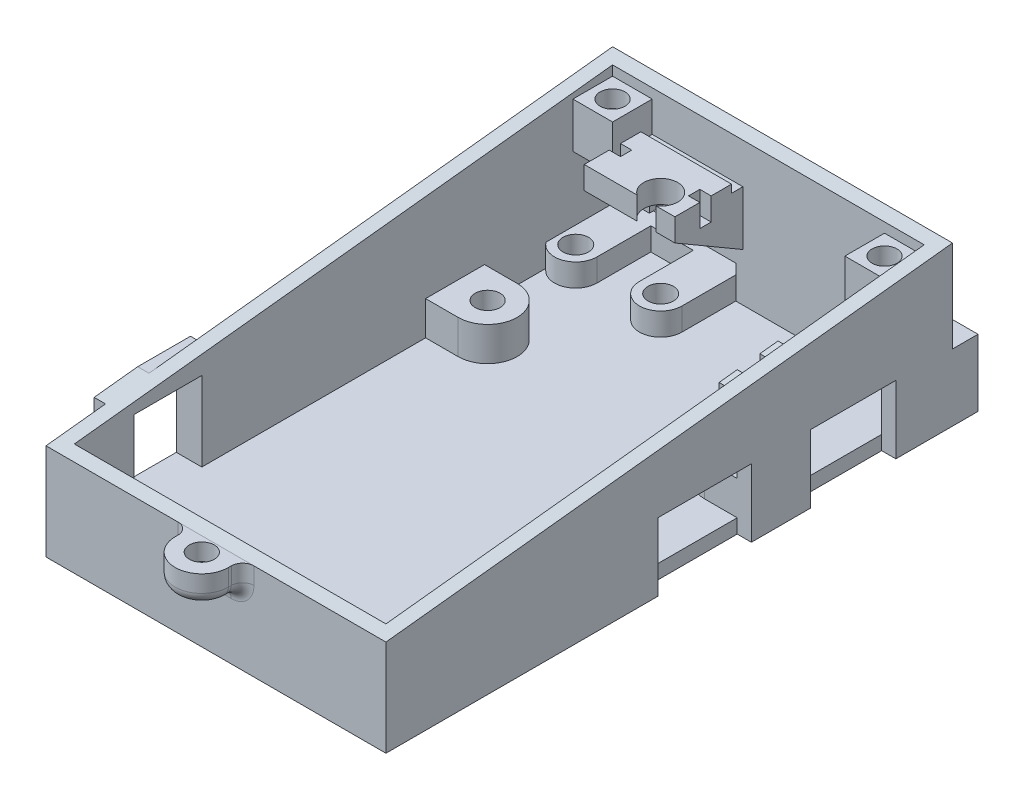
SolidWorks part; units mm, degrees
ref_plane "前视基准面" through (0, 0, 0) normal (0, 0, 1) x (1, 0, 0)
ref_plane "上视基准面" through (0, 0, 0) normal (0, 1, 0) x (1, 0, 0)
ref_plane "右视基准面" through (0, 0, 0) normal (1, 0, 0) x (0, 0, -1)
other "Configuration Table"
sketch "草图1" plane through (0, 0, 0) normal (1, 0, 0) x (0, 0, -1)
  line L0 (0, 0) -> (100, 0)
  line L1 (100, 0) -> (100, 28)
  line L2 (100, 28) -> (0, 17)
  line L3 (0, 17) -> (0, 0)
  dimension "D1" = 100
  dimension "D2" = 28
  dimension "D3" = 17
extrude "凸台-拉伸1" add sketch "草图1" along normal blind 60 contours L3 L0 L1 L2
sketch "草图2" plane through (0, 0, 0) normal (-1, 0, 0) x (0, 0, 1)
  line L0 (0, 17) -> (0, 0) construction
  line L1 (-100, 0) -> (0, 0)
  line L2 (-100, 0) -> (-100, 28)
  line L3 (-97.5, 2.5) -> (-2.5, 2.5)
  line L4 (0, 0) -> (0, 17)
  line L5 (-100, 28) -> (-97.5, 27.725)
  line L6 (-100, 0) -> (-97.5, 0)
  line L7 (-100, 0) -> (-100, 28)
  line L9 (-97.5, 2.5) -> (-97.5, 27.725)
  line L10 (-100, 28) -> (0, 17) construction
  line L11 (-2.5, 17.275) -> (0, 17)
  line L12 (0, 0) -> (-2.5, 0)
  line L13 (0, 0) -> (0, 17)
  line L15 (-2.5, 2.5) -> (-2.5, 17.275)
  dimension "D1" = 2.5
  dimension "D2" = 2.5
  dimension "D3" = 2.5
shell "抽壳1" thickness 2.5
sketch "草图3" plane through (0, 2.5, 0) normal (0, 1, 0) x (1, 0, 0)
  line L0 (30, 97.5) -> (30, 2.5) construction
  line L1 (57.5, 97.5) -> (2.5, 97.5) construction
  line L2 (57.5, 2.5) -> (2.5, 2.5) construction
  line L3 (2.5, 88) -> (64.282, 88) construction
  line L4 (60, 100) -> (0, 100) construction
  line L5 (2.5, 97.5) -> (2.5, 2.5) construction
  line L6 (2.5, 97.5) -> (2.5, 85.75)
  line L7 (2.5, 2.5) -> (2.5, 97.5) construction
  line L8 (9.25, 88) -> (9.25, 97.5)
  line L9 (9.25, 97.5) -> (2.5, 97.5)
  line L10 (16.75, 88) -> (16.75, 97.5)
  line L11 (24.25, 88) -> (24.25, 97.5)
  line L12 (24.25, 97.5) -> (16.75, 97.5)
  line L13 (57.5, 97.5) -> (2.5, 97.5) construction
  circle A0 centre (5.5, 88) radius 2.25
  circle A1 centre (20.5, 88) radius 2.25
  arc A2 (2.5, 85.75) -> (9.25, 88) centre (5.5, 88) ccw
  arc A3 (16.75, 88) -> (24.25, 88) centre (20.5, 88) ccw
  circle A4 centre (5.5, 88) radius 3.75 construction
  circle A5 centre (20.5, 88) radius 3.75 construction
  dimension "D2" = 4.5
  dimension "D1" = 12
  dimension "D3" = 3
  dimension "D4" = 15
  dimension "D5" = 1.5
extrude "凸台-拉伸3" add sketch "草图3" along normal blind 4
sketch "草图4" plane through (0, 0, -97.5) normal (0, 0, 1) x (1, 0, 0)
  line L0 (13, 2.5) -> (13, 21.6286) construction
  line L1 (16.75, 2.5) -> (9.25, 2.5) construction
  line L2 (2.5, 6.5) -> (24.25, 6.5) construction
  line L3 (17, 8.3) -> (24.25, 8.3)
  line L5 (9, 8.3) -> (9, 13)
  line L6 (9, 13) -> (17, 13)
  line L7 (17, 8.3) -> (17, 13)
  line L8 (2.5, 6.5) -> (24.25, 6.5)
  line L9 (2.5, 6.5) -> (2.5, 8.3)
  line L10 (2.5, 8.3) -> (9, 8.3)
  line L11 (24.25, 6.5) -> (24.25, 8.3)
  dimension "D1" = 8
  dimension "D2" = 6.5
  dimension "D3" = 1.8
extrude "切除-拉伸1" cut sketch "草图4" against normal through all
sketch "草图5" plane through (0, 2.5, 0) normal (0, 1, 0) x (1, 0, 0)
  line L0 (30, 2.5) -> (30, 97.5) construction
  line L1 (57.5, 2.5) -> (2.5, 2.5) construction
  line L2 (57.5, 97.5) -> (2.5, 97.5) construction
  line L3 (57.5, 2.5) -> (2.5, 2.5) construction
  line L4 (8.25, 2.5) -> (8.25, 69.7) construction
  line L5 (51.75, 2.5) -> (51.75, 69.7) construction
  line L6 (5.0329, 2.5) -> (11.4671, 2.5)
  line L7 (48.5329, 2.5) -> (54.9671, 2.5)
  line L8 (8.25, 74.9) -> (2.5, 74.9)
  line L9 (2.5, 97.5) -> (2.5, 2.5) construction
  line L10 (2.5, 74.9) -> (2.5, 64.5)
  line L11 (2.5, 2.5) -> (2.5, 85.75) construction
  line L12 (2.5, 64.5) -> (8.25, 64.5)
  line L13 (51.75, 74.9) -> (57.5, 74.9)
  line L14 (57.5, 74.9) -> (57.5, 64.5)
  line L15 (57.5, 64.5) -> (51.75, 64.5)
  circle A0 centre (8.25, 5.2) radius 2.2
  circle A1 centre (51.75, 5.2) radius 2.2
  arc A2 (11.4671, 2.5) -> (5.0329, 2.5) centre (8.25, 5.2) ccw
  arc A3 (48.5329, 2.5) -> (54.9671, 2.5) centre (51.75, 5.2) cw
  circle A4 centre (8.25, 5.2) radius 4.2 construction
  circle A5 centre (8.25, 69.7) radius 2.2
  arc A6 (8.25, 64.5) -> (8.25, 74.9) centre (8.25, 69.7) ccw
  circle A7 centre (8.25, 69.7) radius 5.2 construction
  arc A8 (51.75, 64.5) -> (51.75, 74.9) centre (51.75, 69.7) cw
  circle A9 centre (51.75, 69.7) radius 2.2
  dimension "D2" = 4.4
  dimension "D5" = 4.4
  dimension "D8" = 2
  dimension "D1" = 43.5
  dimension "D3" = 2.7
  dimension "D6" = 64.5
  dimension "D4" = 2
  dimension "D7" = 3
extrude "凸台-拉伸4" add sketch "草图5" along normal blind 6
sketch "草图6" plane through (0, 0, 0) normal (-1, 0, 0) x (0, 0, 1)
  line L0 (-100, 0) -> (0, 0) construction
  line L1 (-90, 0) -> (-48, 0)
  line L2 (-90, 0) -> (-90, 12)
  line L3 (-90, 12) -> (-48, 12)
  line L4 (-48, 0) -> (-48, 12)
  line L5 (-100, 0) -> (-100, 28) construction
  dimension "D1" = 10
  dimension "D2" = 52
  dimension "D3" = 12
sketch "草图7" plane through (60, 0, 0) normal (1, 0, 0) x (0, 0, -1)
  line L25 (90, 0) -> (90, 12)
  line L26 (48, 0) -> (90, 0)
  line L27 (48, 12) -> (48, 0)
  line L28 (90, 12) -> (48, 12)
  line L29 (90, 0) -> (90, 12)
  line L30 (48, 0) -> (90, 0)
  line L31 (48, 12) -> (48, 0)
  line L32 (90, 12) -> (48, 12)
  dimension "D1" = 0
extrude "切除-拉伸3" cut sketch "草图7" against normal up to surface (2.5 mm away) up to face at (57.5, 9, -59.85)
sketch "草图8" plane through (57.5, 0, 0) normal (1, 0, 0) x (0, 0, -1)
  line L0 (90, 12) -> (48, 12) construction
  line L1 (64.5, 12) -> (74.9, 12)
  line L2 (64.5, 12) -> (64.5, 0)
  line L3 (64.5, 0) -> (74.9, 0)
  line L4 (74.9, 12) -> (74.9, 0)
  line L5 (100, 0) -> (0, 0) construction
  line L6 (74.9, 8.5) -> (74.9, 2.5) construction
  line L7 (64.5, 8.5) -> (64.5, 2.5) construction
extrude "凸台-拉伸5" add sketch "草图8" along normal up to surface (2.5 mm away) up to face at (60, 8.625, -59.5)
ref_plane "基准面5" through (0, 28, 0) normal (0, 1, 0) x (1, 0, 0)
ref_plane "基准面6" through (0, 18, 0) normal (0, 1, 0) x (1, 0, 0)
sketch "草图9" plane through (0, 18, 0) normal (0, 1, 0) x (1, 0, 0)
  line L0 (2.5, 94) -> (9.5, 94) construction
  line L1 (2.5, 97.5) -> (9.5, 97.5)
  line L2 (2.5, 97.5) -> (2.5, 90.5)
  line L3 (2.5, 90.5) -> (9.5, 90.5)
  line L4 (9.5, 97.5) -> (9.5, 90.5)
  line L5 (6, 97.5) -> (6, 90.5) construction
  circle A0 centre (6, 94) radius 2.2
  dimension "D1" = 4.4
  dimension "D2" = 7
  dimension "D3" = 7
extrude "凸台-拉伸6" add sketch "草图9" along normal offset from surface (8 mm away) 2 up to plane "基准面5"
sketch "草图10" plane through (0, 18, 0) normal (0, -1, 0) x (1, 0, 0)
  circle A0 centre (6, -94) radius 2.2
extrude "凸台-拉伸7" add sketch "草图10" against normal blind 5
sketch "草图11" plane through (0, 18, 0) normal (0, -1, 0) x (1, 0, 0)
  line L0 (17.5, -85.5) -> (17.5, -97.5) construction
  line L1 (9.5, -97.5) -> (25.5, -97.5)
  line L2 (9.5, -97.5) -> (9.5, -91.9)
  line L3 (9.5, -85.5) -> (25.5, -85.5)
  line L4 (25.5, -97.5) -> (25.5, -91.9)
  line L5 (9.5, -89.9) -> (11.5, -89.9)
  line L7 (9.5, -91.9) -> (11.5, -91.9)
  line L8 (11.5, -89.9) -> (11.5, -91.9)
  line L9 (25.5, -89.9) -> (23.5, -89.9)
  line L11 (25.5, -91.9) -> (23.5, -91.9)
  line L12 (23.5, -89.9) -> (23.5, -91.9)
  line L13 (25.5, -89.9) -> (25.5, -85.5)
  line L14 (9.5, -89.9) -> (9.5, -85.5)
  dimension "D1" = 16
  dimension "D2" = 12
  dimension "D3" = 2
  dimension "D4" = 12
  dimension "D5" = 5.6
extrude "凸台-拉伸8" add sketch "草图11" against normal offset from surface (4 mm away) 4 up to face at (6, 26, -91.8)
sketch "草图13" plane through (25.5, 0, 0) normal (1, 0, 0) x (0, 0, -1)
  line L0 (85.5, 18) -> (97.5, 11)
  line L1 (33, 18) -> (-33, 18) construction
  line L2 (97.5, 2.5) -> (97.5, 27.725) construction
  line L3 (97.5, 11) -> (97.5, 18)
  line L4 (97.5, 18) -> (85.5, 18)
  line L5 (85.5, 22) -> (85.5, 18) construction
  dimension "D1" = 7
extrude "凸台-拉伸10" add sketch "草图13" against normal blind 4
sketch "草图14" plane through (0, 6.5, 0) normal (0, 1, 0) x (1, 0, 0)
  circle A0 centre (20.5, 88) radius 3
  dimension "D1" = 6
extrude "切除-拉伸4" cut sketch "草图14" along normal through all
sketch "草图15" plane through (0, 22, 0) normal (0, 1, 0) x (1, 0, 0)
  line L0 (25.5, 97.5) -> (25.5, 91.9) construction
  line L1 (9.5, 97.5) -> (25.5, 97.5)
  line L2 (9.5, 97.5) -> (9.5, 95.5)
  line L3 (9.5, 95.5) -> (25.5, 95.5)
  line L4 (25.5, 97.5) -> (25.5, 95.5)
  dimension "D1" = 2
extrude "切除-拉伸5" cut sketch "草图15" against normal blind 1.4
ref_plane "基准面7" through (30, 0, 0) normal (-1, 0, 0) x (0, 0, 1)
mirror "镜向2" about plane through (30, 0, 0) normal (-1, 0, 0) of "凸台-拉伸6"
sketch "草图16" plane through (0, 0, 0) normal (-1, 0, 0) x (0, 0, 1)
  line L0 (-97.5, 2.5) -> (-2.5, 2.5) construction
  line L1 (-13, 16.5) -> (-25, 16.5)
  line L2 (-13, 16.5) -> (-13, 2.5)
  line L3 (-13, 2.5) -> (-25, 2.5)
  line L4 (-25, 16.5) -> (-25, 2.5)
  line L5 (0, 0) -> (0, 17) construction
  dimension "D1" = 13
  dimension "D2" = 12
  dimension "D3" = 14
extrude "切除-拉伸6" cut sketch "草图16" against normal up to surface (2.5 mm away)
sketch "草图17" plane through (0, 0, 0) normal (-1, 0, 0) x (0, 0, 1)
  line L0 (-27.5, 0) -> (-10.5, 0)
  line L1 (-25, 2.5) -> (-13, 2.5)
  line L2 (-25, 2.5) -> (-25, 16.5)
  line L3 (-25, 16.5) -> (-13, 16.5)
  line L4 (-13, 2.5) -> (-13, 16.5)
  line L5 (-10.5, 0) -> (-10.5, 18.155)
  line L6 (-27.5, 19) -> (-18.1818, 19)
  line L7 (-27.5, 0) -> (-27.5, 19)
  line L8 (-18.1818, 19) -> (-10.5, 18.155)
  line L9 (-100, 28) -> (0, 17) construction
  line L10 (-10.5, 0) -> (-10.5, 19) construction
  line L11 (-27.5, 19) -> (-10.5, 19) construction
  dimension "D1" = 2.5
extrude "凸台-拉伸14" add sketch "草图17" along normal blind 2
sketch "草图18" plane through (0, 8.5, 0) normal (0, 1, 0) x (1, 0, 0)
  line L1 (57.5, 74.9) -> (54.3, 74.9)
  line L2 (57.5, 74.9) -> (57.5, 71.7)
  line L3 (57.5, 71.7) -> (54.3, 71.7)
  line L4 (54.3, 74.9) -> (54.3, 71.7)
  line L5 (57.5, 64.5) -> (54.3, 64.5)
  line L6 (57.5, 64.5) -> (57.5, 67.7)
  line L7 (57.5, 67.7) -> (54.3, 67.7)
  line L8 (54.3, 64.5) -> (54.3, 67.7)
  dimension "D1" = 3.2
extrude "凸台-拉伸15" add sketch "草图18" along normal offset from surface (14.2239 mm away) 2.5
sketch "草图19" plane through (0, 8.5, 0) normal (0, 1, 0) x (1, 0, 0)
  line L1 (57.5, 74.9) -> (51.75, 74.9)
  line L2 (57.5, 74.9) -> (57.5, 64.5)
  line L3 (57.5, 64.5) -> (51.75, 64.5)
  line L4 (51.75, 74.9) -> (51.75, 64.5)
extrude "切除-拉伸7" cut sketch "草图19" along normal blind 4
sketch "草图20" plane through (0, 0, -2.5) normal (0, 0, -1) x (-1, 0, 0)
  line L0 (-57.5, 17.275) -> (-57.5, 2.5) construction
  line L1 (-57.5, 8.5) -> (-2.5, 8.5)
  line L2 (-57.5, 8.5) -> (-57.5, 11.5)
  line L3 (-57.5, 11.5) -> (-2.5, 11.5)
  line L4 (-2.5, 8.5) -> (-2.5, 11.5)
  line L5 (-2.5, 17.275) -> (-2.5, 2.5) construction
  line L6 (-48.5329, 8.5) -> (-54.9671, 8.5) construction
  dimension "D1" = 3
extrude "切除-拉伸8" cut sketch "草图20" against normal blind 0.5
sketch "草图21" plane through (0, 0, 0) normal (0, 0, 1) x (1, 0, 0)
  line L0 (60, 17) -> (0, 17) construction
  line L1 (26, 17) -> (34, 17)
  line L2 (26, 17) -> (26, 12)
  line L3 (26, 12) -> (34, 12)
  line L4 (34, 17) -> (34, 12)
  line L5 (30, 0) -> (30, 17) construction
  line L6 (60, 0) -> (0, 0) construction
  dimension "D1" = 8
  dimension "D2" = 5
ref_plane "基准面8" through (0, 17, 0) normal (0, 1, 0) x (1, 0, 0)
sketch "草图22" plane through (0, 17, 0) normal (0, 1, 0) x (1, 0, 0)
  line L0 (30, 13.8738) -> (30, -13.8738) construction
  line L1 (60, 0) -> (0, 0) construction
  line L2 (25.3, -2.5) -> (25.3, 0)
  line L3 (25.3, 0) -> (34.7, 0)
  line L4 (34.7, 0) -> (34.7, -2.5)
  circle A0 centre (30, -2.5) radius 2.2
  arc A1 (25.3, -2.5) -> (34.7, -2.5) centre (30, -2.5) ccw
  circle A2 centre (30, -2.5) radius 4.7 construction
  point P7 (30, -5.2449)
  dimension "D1" = 4.4
  dimension "D3" = 2.5
  dimension "D2" = 2.5
extrude "凸台-拉伸17" add sketch "草图22" against normal blind 5
sketch "草图23" plane through (0, 12, 0) normal (0, -1, 0) x (1, 0, 0)
  circle A0 centre (30, 2.5) radius 2.8974
extrude "凸台-拉伸18" add sketch "草图23" against normal offset from surface (2 mm away) 3 up to face at (30, 17, 4.7)
fillet "圆角1" radius 2 6 edges at (34.7, 14.5, 0) (25.3, 14.5, 0) (30, 12, 7.2) (34.7, 12, 1.25) (30, 12, 0) (25.3, 12, 1.25)
sketch "草图25" plane through (0, 0, -100) normal (0, 0, -1) x (-1, 0, 0)
  line L0 (-60, 0) -> (-60, 28) construction
  line L1 (-57, 3) -> (-51.2, 3)
  line L2 (-57, 3) -> (-57, 8.8)
  line L3 (-57, 8.8) -> (-51.2, 8.8)
  line L4 (-51.2, 3) -> (-51.2, 8.8)
  line L5 (-60, 0) -> (0, 0) construction
  dimension "D1" = 3
  dimension "D2" = 3
  dimension "D3" = 5.8
extrude "切除-拉伸9" cut sketch "草图25" against normal up to next
sketch "草图26" plane through (0, 0, -97.5) normal (0, 0, 1) x (1, 0, 0)
  line L0 (57, 5.9) -> (51.2, 5.9) construction
  line L1 (57, 8.8) -> (57, 3) construction
  line L2 (51.2, 3) -> (51.2, 8.8) construction
  line L4 (57, 3.9) -> (51.2, 3.9)
  line L5 (57, 3.9) -> (57, 7.9)
  line L6 (57, 7.9) -> (51.2, 7.9)
  line L7 (51.2, 3.9) -> (51.2, 7.9)
  dimension "D1" = 4
extrude "凸台-拉伸19" add sketch "草图26" against normal blind 1
sketch "草图27" plane through (0, 0, -97.5) normal (0, 0, 1) x (1, 0, 0)
  line L0 (57, 7.9) -> (51.2, 7.9) construction
  line L1 (59.1, 7.9) -> (49.1, 7.9)
  line L2 (59.1, 7.9) -> (59.1, 3.9)
  line L3 (59.1, 3.9) -> (49.1, 3.9)
  line L4 (49.1, 7.9) -> (49.1, 3.9)
  line L5 (51.2, 3.9) -> (57, 3.9) construction
  line L6 (54.1, 8.8) -> (54.1, 3) construction
  line L7 (51.2, 8.8) -> (57, 8.8) construction
  line L8 (57, 3) -> (51.2, 3) construction
  dimension "D1" = 10
extrude "凸台-拉伸20" add sketch "草图27" along normal blind 2
sketch "草图28" plane through (0, 0, -100) normal (0, 0, -1) x (-1, 0, 0)
  line L19 (-48.2, 11.8) -> (-60, 11.8)
  line L20 (-48.2, 0) -> (-48.2, 11.8)
  line L21 (-60, 0) -> (-48.2, 0)
  line L22 (-60, 11.8) -> (-60, 0)
  line L23 (-48.2, 11.8) -> (-60, 11.8)
  line L24 (-48.2, 0) -> (-48.2, 11.8)
  line L25 (-60, 0) -> (-48.2, 0)
  line L26 (-60, 11.8) -> (-60, 0)
  line L37 (-51.2, 3) -> (-51.2, 8.8)
  line L38 (-57, 3) -> (-51.2, 3)
  line L39 (-57, 8.8) -> (-57, 3)
  line L40 (-51.2, 8.8) -> (-57, 8.8)
  line L41 (-51.2, 3) -> (-51.2, 8.8)
  line L42 (-57, 3) -> (-51.2, 3)
  line L43 (-57, 8.8) -> (-57, 3)
  line L44 (-51.2, 8.8) -> (-57, 8.8)
  line M9 (-51.2, 8.8) -> (-51.2, 3)
  line M10 (-51.2, 3) -> (-57, 3)
  line M11 (-57, 3) -> (-57, 8.8)
  line M12 (-57, 8.8) -> (-51.2, 8.8)
  line M23 (-60, 28) -> (-60, 0)
  line M24 (-60, 0) -> (0, 0)
  dimension "D1" = 3
  dimension "D2" = 0
extrude "凸台-拉伸23" add sketch "草图28" along normal blind 4.5 contours L24 L23 M24 M23 M12 M9 M10 M11 | L41 L44 L43 L42
equation "\"2。5\"=2.31968"
